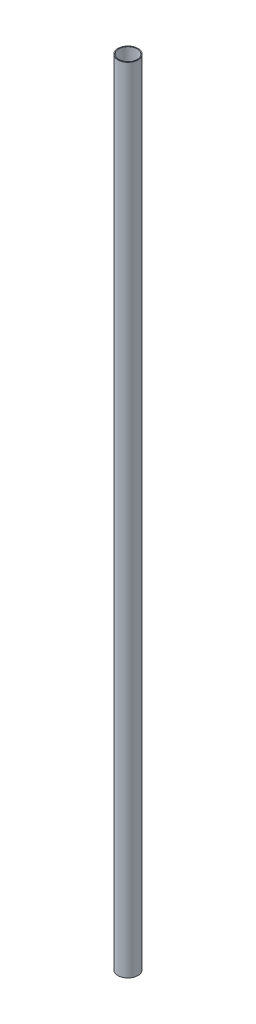
SolidWorks part; units mm, degrees
ref_plane "Front Plane" through (0, 0, 0) normal (0, 0, 1) x (1, 0, 0)
ref_plane "Top Plane" through (0, 0, 0) normal (0, 1, 0) x (1, 0, 0)
ref_plane "Right Plane" through (0, 0, 0) normal (1, 0, 0) x (0, 0, -1)
sketch "Sketch2" plane through (0, 0, 0) normal (0, 1, 0) x (1, 0, 0)
  circle A0 centre (0, 0) radius 15
  circle A1 centre (0, 0) radius 16.3815
extrude "Boss-Extrude1" add sketch "Sketch2" along normal blind 1296.555
